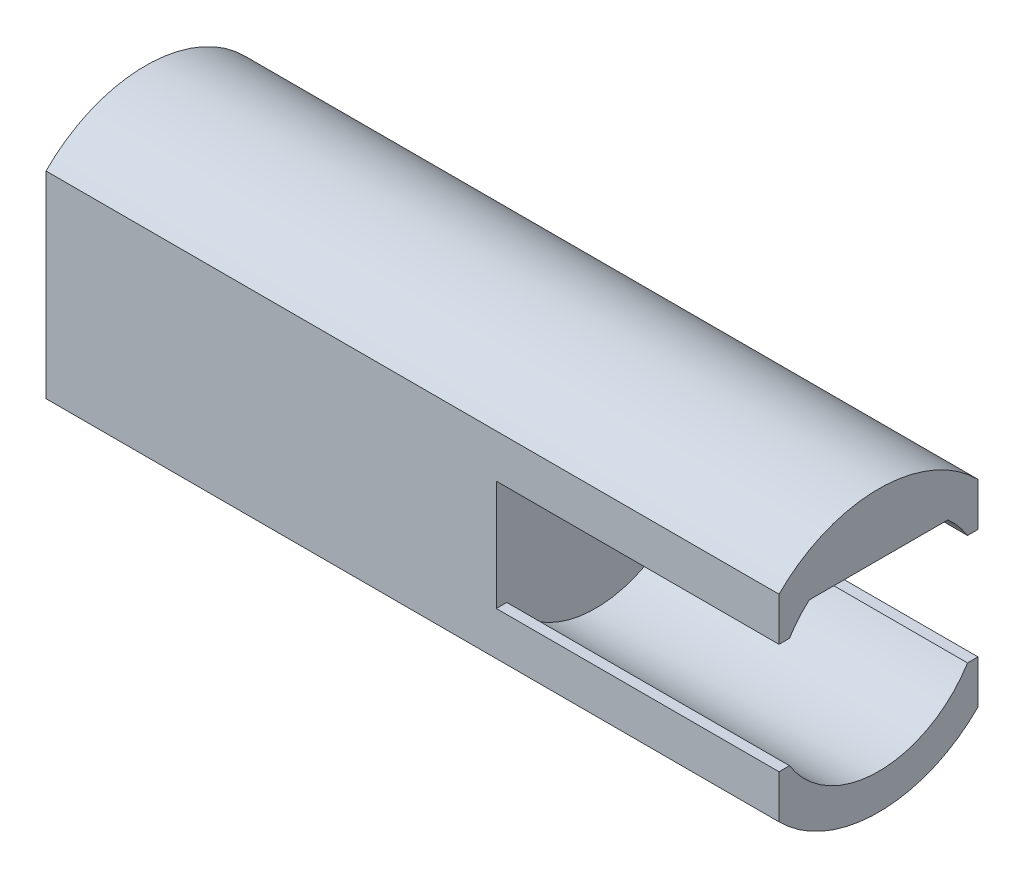
SolidWorks part; units mm, degrees
ref_plane "Front Plane" through (0, 0, 0) normal (0, 0, 1) x (1, 0, 0)
ref_plane "Top Plane" through (0, 0, 0) normal (0, 1, 0) x (1, 0, 0)
ref_plane "Right Plane" through (0, 0, 0) normal (1, 0, 0) x (0, 0, -1)
sketch "Sketch1" plane through (0, 0, 0) normal (1, 0, 0) x (0, 0, -1)
  line L0 (-1.9, 1.883) -> (-1.9, -1.883)
  line L1 (1.9, 1.883) -> (1.9, -1.883)
  line L2 (-1.3229, 1.5) -> (1.3229, 1.5)
  arc A0 (-1.9, -1.883) -> (1.9, -1.883) centre (0, 0) ccw
  arc A2 (1.9, 1.883) -> (-1.9, 1.883) centre (0, 0) ccw
  arc A3 (-1.3229, 1.5) -> (1.3229, 1.5) centre (0, 0) ccw
  point P9 (0, -2)
  dimension "D3" = 5.35
  dimension "D4" = 4
  dimension "D1" = 3.8
  dimension "D2" = 1.9
  dimension "D5" = 1.5
sketch "Sketch2" plane through (0, 0, 0) normal (1, 0, 0) x (0, 0, -1)
  line L0 (-1.9, -1.883) -> (-1.9, -1.0536)
  line L2 (-1.9, 1.883) -> (-1.9, 1.0536)
  line L3 (1.9, 1.883) -> (1.9, 1.0536)
  line L5 (1.9, -1.883) -> (1.9, -1.0536)
  line L6 (-1.9, 1.0536) -> (-1.7, 1.0536)
  line L7 (1.7, 1.0536) -> (1.9, 1.0536)
  line L8 (-1.9, -1.0536) -> (-1.7, -1.0536)
  line L9 (1.7, -1.0536) -> (1.9, -1.0536)
  line L10 (-1.3229, 1.5) -> (1.3229, 1.5)
  arc A0 (-1.9, 1.883) -> (1.9, 1.883) centre (0, 0) cw
  arc A1 (1.9, 1.883) -> (-1.9, 1.883) centre (0, 0) ccw construction
  arc A2 (-1.9, -1.883) -> (1.9, -1.883) centre (0, 0) ccw
  arc A3 (-1.9, -1.883) -> (1.9, -1.883) centre (0, 0) ccw construction
  arc A4 (-1.7, -1.0536) -> (1.7, -1.0536) centre (0, 0) ccw
  circle A5 centre (0, 0) radius 2 construction
  arc A6 (1.7, 1.0536) -> (1.3229, 1.5) centre (0, 0) ccw
  arc A7 (-1.3229, 1.5) -> (-1.7, 1.0536) centre (0, 0) ccw
  dimension "D1" = 0.2
  dimension "D2" = 0.2
extrude "Boss-Extrude1" add sketch "Sketch2" along normal blind 5.4
ref_plane "Plane1" through (-8.6, 0, 0) normal (1, 0, 0) x (0, 0, -1)
sketch "Sketch3" plane through (0, 0, 0) normal (-1, 0, 0) x (0, 0, 1)
  line L9 (1.9, -1.883) -> (1.9, 1.883)
  line L10 (-1.9, 1.883) -> (-1.9, -1.883)
  line L11 (1.9, -1.883) -> (1.9, 1.883)
  line L12 (-1.9, 1.883) -> (-1.9, -1.883)
  arc A8 (-1.9, -1.883) -> (1.9, -1.883) centre (0, 0) ccw
  arc A9 (1.9, 1.883) -> (-1.9, 1.883) centre (0, 0) ccw
  arc A10 (-1.9, -1.883) -> (1.9, -1.883) centre (0, 0) ccw
  arc A11 (1.9, 1.883) -> (-1.9, 1.883) centre (0, 0) ccw
  dimension "D1" = 0
extrude "Boss-Extrude2" add sketch "Sketch3" along direction (1, 0, 0) on the side of the normal up to surface (8.6 mm away) up to plane "Plane1"
equation "\"D2@Sketch1\"=\"D1@Sketch1\"/2"
